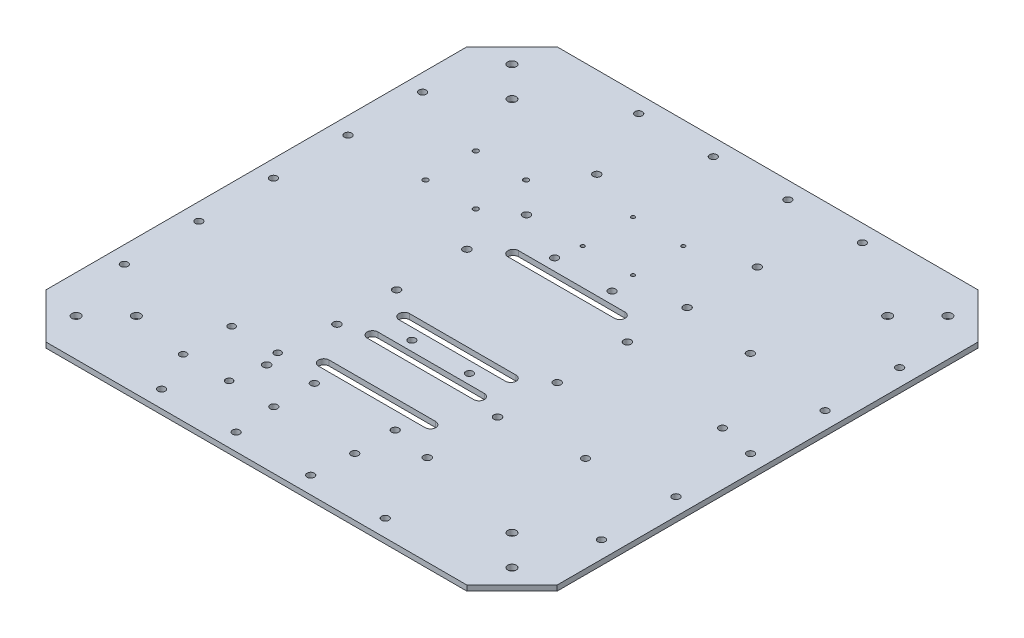
SolidWorks part; units mm, degrees
ref_plane "Front Plane" through (0, 0, 0) normal (0, 0, 1) x (1, 0, 0)
ref_plane "Top Plane" through (0, 0, 0) normal (0, 1, 0) x (1, 0, 0)
ref_plane "Right Plane" through (0, 0, 0) normal (1, 0, 0) x (0, 0, -1)
sketch "Sketch1" plane through (0, 0, 0) normal (0, 1, 0) x (1, 0, 0)
  line L0 (-121.2861, 45.3182) -> (-94.3453, 72.259)
  line L1 (-121.2861, 72.259) -> (183.5139, 72.259)
  line L2 (-121.2861, 72.259) -> (-121.2861, -232.541)
  line L3 (-121.2861, -232.541) -> (183.5139, -232.541)
  line L4 (183.5139, 72.259) -> (183.5139, -232.541)
  line L5 (31.1139, 95.069) -> (31.1139, -294.9418) construction
  line L6 (-146.0448, -80.141) -> (218.038, -80.141) construction
  line L7 (183.5139, 45.3182) -> (156.5732, 72.259)
  line L8 (183.5139, -205.6003) -> (156.5732, -232.541)
  line L9 (-121.2861, -205.6003) -> (-94.3453, -232.541)
  point P8 (31.1139, 72.259)
  point P11 (-121.2861, -80.141)
  dimension "D1" = 304.8
  dimension "D2" = 304.8
  dimension "D3" = 45
  dimension "D4" = 38.1
extrude "Boss-Extrude1" add sketch "Sketch1" along normal blind 3.175
sketch "Sketch2" plane through (0, 3.175, 0) normal (0, 1, 0) x (1, 0, 0)
  line L0 (31.1139, 72.259) -> (31.1139, -287.8465) construction
  line L1 (-94.3453, 72.259) -> (156.5732, 72.259) construction
  line L2 (183.5139, -80.141) -> (-158.2106, -80.141) construction
  line L3 (183.5139, 45.3182) -> (183.5139, -205.6003) construction
  circle A0 centre (13.8419, -37.469) radius 2.159
  circle A1 centre (48.1319, -37.469) radius 2.159
  circle A2 centre (13.8419, -122.559) radius 2.159
  circle A3 centre (48.1319, -122.559) radius 2.159
  dimension "D5" = 4.318
  dimension "D6" = 4.318
  dimension "D7" = 4.318
  dimension "D8" = 4.318
  dimension "D1" = 17.272
  dimension "D2" = 34.29
  dimension "D3" = 85.09
  dimension "D4" = 42.672
extrude "Cut-Extrude1" cut sketch "Sketch2" against normal through all
sketch "Sketch4" plane through (0, 3.175, 0) normal (0, 1, 0) x (1, 0, 0)
  line L0 (-0.6361, -47.641) -> (62.8639, -47.641) construction
  line L1 (-0.6361, -44.466) -> (62.8639, -44.466)
  line L2 (-0.6361, -50.816) -> (62.8639, -50.816)
  line L3 (-0.6361, -112.641) -> (62.8639, -112.641) construction
  line L4 (-0.6361, -109.466) -> (62.8639, -109.466)
  line L5 (-0.6361, -115.816) -> (62.8639, -115.816)
  line L6 (183.5139, 45.3182) -> (183.5139, -205.6003) construction
  line L8 (-121.2861, -80.141) -> (183.5139, -80.141) construction
  line L9 (-121.2861, 45.3182) -> (-121.2861, -205.6003) construction
  line L11 (-0.6361, -131.576) -> (62.8639, -131.576) construction
  line L12 (-0.6361, -128.401) -> (62.8639, -128.401)
  line L13 (-0.6361, -134.751) -> (62.8639, -134.751)
  line L14 (-0.6361, -160.576) -> (62.8639, -160.576) construction
  line L15 (-0.6361, -157.401) -> (62.8639, -157.401)
  line L16 (-0.6361, -163.751) -> (62.8639, -163.751)
  line L17 (31.1139, -47.641) -> (31.1139, -112.641) construction
  arc A0 (-0.6361, -44.466) -> (-0.6361, -50.816) centre (-0.6361, -47.641) ccw
  arc A1 (62.8639, -50.816) -> (62.8639, -44.466) centre (62.8639, -47.641) ccw
  arc A2 (-0.6361, -109.466) -> (-0.6361, -115.816) centre (-0.6361, -112.641) ccw
  arc A3 (62.8639, -115.816) -> (62.8639, -109.466) centre (62.8639, -112.641) ccw
  arc A5 (-0.6361, -128.401) -> (-0.6361, -134.751) centre (-0.6361, -131.576) ccw
  arc A6 (62.8639, -134.751) -> (62.8639, -128.401) centre (62.8639, -131.576) ccw
  arc A7 (-0.6361, -157.401) -> (-0.6361, -163.751) centre (-0.6361, -160.576) ccw
  arc A8 (62.8639, -163.751) -> (62.8639, -157.401) centre (62.8639, -160.576) ccw
  point P2 (31.1139, -47.641)
  point P7 (31.1139, -112.641)
  point P14 (183.5139, -80.141)
  point P15 (31.1139, 72.259)
  point P18 (31.1139, -80.141)
  point P19 (31.1139, -80.141)
  point P28 (31.1139, -131.576)
  point P33 (31.1139, -160.576)
  point P40 (0, 0)
  point P41 (31.1139, -30.0806)
  point P42 (31.1139, 72.259)
  point P43 (31.1139, -28.4758)
  dimension "D1" = 63.5
  dimension "D2" = 63.5
  dimension "D3" = 6.35
  dimension "D4" = 6.35
  dimension "D5" = 65
  dimension "D7" = 63.5
  dimension "D8" = 63.5
  dimension "D9" = 6.35
  dimension "D10" = 6.35
  dimension "D11" = 29
  dimension "D12" = 48.26
extrude "Cut-Extrude2" cut sketch "Sketch4" against normal through all
sketch "Sketch7" plane through (0, 3.175, 0) normal (0, 1, 0) x (1, 0, 0)
  line L0 (-49.9121, 83.1696) -> (-49.9121, -30.4318) construction
  line L1 (-121.2861, -80.141) -> (183.5139, -80.141) construction
  line L2 (-121.2861, 45.3182) -> (-121.2861, -205.6003) construction
  line L3 (183.5139, 45.3182) -> (183.5139, -205.6003) construction
  line L4 (31.1139, 72.259) -> (31.1139, -252.674) construction
  line L5 (-94.3453, 72.259) -> (156.5732, 72.259) construction
  circle A0 centre (-34.9261, -5.719) radius 1.524
  circle A1 centre (-34.9261, -35.691) radius 1.524
  circle A2 centre (-64.8981, -35.691) radius 1.524
  circle A3 centre (-64.8981, -5.719) radius 1.524
  dimension "D1" = 3.048
  dimension "D2" = 14.986
  dimension "D4" = 29.972
  dimension "D3" = 3.048
  dimension "D5" = 44.45
  dimension "D6" = 66.04
  dimension "D7" = 14.986
extrude "Cut-Extrude3" cut sketch "Sketch7" against normal through all
sketch "Sketch8" plane through (0, 3.175, 0) normal (0, 1, 0) x (1, 0, 0)
  line L0 (-94.3453, -232.541) -> (156.5732, -232.541) construction
  line L1 (183.5139, 45.3182) -> (183.5139, -205.6003) construction
  circle A0 centre (73.0239, -207.649) radius 1.524
  circle A1 centre (73.0239, -177.169) radius 1.524
  circle A2 centre (96.8999, -207.649) radius 1.524
  circle A3 centre (96.8999, -177.169) radius 1.524
  dimension "D1" = 3.048
  dimension "D2" = 30.48
  dimension "D3" = 23.876
  dimension "D4" = 24.892
  dimension "D5" = 86.614
extrude "Cut-Extrude4" [suppressed] cut sketch "Sketch8" against normal through all and the other way through all
sketch "Sketch10" plane through (0, 0, 0) normal (0, -1, 0) x (1, 0, 0)
  line L0 (-94.3453, 232.541) -> (156.5732, 232.541) construction
  line L1 (31.1139, 232.541) -> (31.1139, 128.7119) construction
  line L2 (-0.6361, 163.751) -> (62.8639, 163.751) construction
  circle A0 centre (6.9839, 198.041) radius 2.159
  circle A1 centre (55.2439, 198.041) radius 2.159
  circle A2 centre (6.9839, 173.911) radius 2.159
  circle A3 centre (55.2439, 173.911) radius 2.159
  dimension "D1" = 4.318
  dimension "D2" = 48.26
  dimension "D4" = 10.16
  dimension "D6" = 4.318
  dimension "D7" = 4.318
  dimension "D8" = 4.318
  dimension "D3" = 24.13
  dimension "D5" = 24.13
extrude "Cut-Extrude6" cut sketch "Sketch10" against normal through all
sketch "Sketch9" plane through (0, 0, 0) normal (0, -1, 0) x (-1, 0, 0)
  line L1 (121.2861, -80.141) -> (-327.4314, -80.141) construction
  line L2 (33.4021, -47.3693) -> (33.4021, -130.2963) construction
  line L3 (-31.1139, 72.259) -> (-31.1139, -331.7119) construction
  line L4 (94.3453, 72.259) -> (-156.5732, 72.259) construction
  line L7 (121.2861, 45.3182) -> (121.2861, -205.6003) construction
  circle A0 centre (47.1181, -197.997) radius 2.032
  circle A1 centre (19.6861, -197.997) radius 2.032
  circle A2 centre (47.1181, -169.041) radius 2.032
  circle A3 centre (19.6861, -169.041) radius 2.032
  dimension "D1" = 4.064
  dimension "D9" = 4.064
  dimension "D2" = 50.8
  dimension "D3" = 28.956
  dimension "D4" = 88.9
  dimension "D8" = 13.716
extrude "Cut-Extrude5" cut sketch "Sketch9" against normal through all
sketch "Sketch13" plane through (0, 0, 0) normal (0, -1, 0) x (1, 0, 0)
  line L0 (31.1139, -72.259) -> (31.1139, 261.4711) construction
  line L1 (-94.3453, -72.259) -> (156.5732, -72.259) construction
  line L2 (-121.2861, 80.141) -> (239.2508, 80.141) construction
  line L3 (-121.2861, -45.3182) -> (-121.2861, 205.6003) construction
  circle A0 centre (16.1139, 22.991) radius 1.1
  circle A1 centre (16.1139, -7.009) radius 1.1
  circle A2 centre (46.1139, -7.009) radius 1.1
  circle A3 centre (46.1139, 22.991) radius 1.1
  point P16 (0, 0)
  dimension "D1" = 2.2
  dimension "D2" = 2.2
  dimension "D3" = 30
  dimension "D4" = 15
  dimension "D5" = 57.15
extrude "Cut-Extrude8" cut sketch "Sketch13" against normal through all
sketch "Sketch14" plane through (0, 0, 0) normal (0, -1, 0) x (1, 0, 0)
  line L0 (31.1139, 232.541) -> (31.1139, -154.5354) construction
  line L1 (-94.3453, 232.541) -> (156.5732, 232.541) construction
  line L2 (-121.2861, 80.141) -> (331.9066, 80.141) construction
  line L3 (-121.2861, -45.3182) -> (-121.2861, 205.6003) construction
  line L4 (-121.2861, 205.6003) -> (-94.3453, 232.541) construction
  line L5 (-224.559, -175.5319) -> (286.7869, 335.814) construction
  line L6 (-224.559, -175.5319) -> (286.7869, -175.5319) construction
  line L7 (-224.559, -175.5319) -> (-224.559, 335.814) construction
  line L8 (-121.2861, 205.6003) -> (-94.3453, 232.541) construction
  line L9 (-107.8157, 219.0706) -> (-48.5429, 159.7979) construction
  line L10 (-224.559, 335.814) -> (286.7869, 335.814) construction
  line L11 (286.7869, -175.5319) -> (286.7869, 335.814) construction
  line L12 (286.7869, -175.5319) -> (-224.559, 335.814) construction
  line L14 (-121.2861, -45.3182) -> (-94.3453, -72.259) construction
  line L21 (-224.559, -175.5319) -> (-107.8157, -58.7886) construction
  line L22 (170.0436, -58.7886) -> (286.7869, -175.5319) construction
  line L23 (183.5139, -45.3182) -> (156.5732, -72.259) construction
  line L24 (170.0436, 219.0706) -> (286.7869, 335.814) construction
  line L25 (183.5139, 205.6003) -> (156.5732, 232.541) construction
  line L26 (-224.559, 335.814) -> (-107.8157, 219.0706) construction
  circle A1 centre (-98.8354, 210.0904) radius 2.54
  circle A3 centre (-80.8749, 192.1299) radius 2.54
  circle A4 centre (143.1028, 192.1299) radius 2.54
  circle A7 centre (161.0633, 210.0904) radius 2.54
  circle A8 centre (-98.8354, -49.8083) radius 2.54
  circle A11 centre (-80.8749, -31.8478) radius 2.54
  circle A14 centre (161.0633, -49.8083) radius 2.54
  circle A15 centre (143.1028, -31.8478) radius 2.54
  point P8 (31.1139, 80.141)
  point P30 (286.7869, 80.141)
  point P33 (-107.8157, -58.7886)
  point P36 (31.1139, -175.5319)
  dimension "D3" = 5.08
  dimension "D6" = 5.08
  dimension "D1" = 12.7
  dimension "D2" = 165.1
  dimension "D9" = 25.4
extrude "Cut-Extrude9" cut sketch "Sketch14" against normal through all
sketch "Sketch15" plane through (0, 0, 0) normal (0, -1, 0) x (1, 0, 0)
  line L0 (31.1139, 232.541) -> (31.1139, 125.875) construction
  line L1 (-94.3453, 232.541) -> (156.5732, 232.541) construction
  line L2 (-121.2861, 80.141) -> (75.4631, 80.141) construction
  line L3 (-121.2861, -45.3182) -> (-121.2861, 205.6003) construction
  circle A0 centre (8.8889, 222.381) radius 2.159
  circle A1 centre (-35.5611, 222.381) radius 2.159
  circle A2 centre (-111.1261, 80.141) radius 2.159
  circle A3 centre (-111.1261, 124.591) radius 2.159
  circle A4 centre (-111.1261, 169.041) radius 2.159
  circle A5 centre (173.3539, 169.041) radius 2.159
  circle A6 centre (173.3539, 124.591) radius 2.159
  circle A7 centre (173.3539, 80.141) radius 2.159
  circle A8 centre (97.7889, 222.381) radius 2.159
  circle A9 centre (53.3389, 222.381) radius 2.159
  circle A10 centre (53.3389, -62.099) radius 2.159
  circle A11 centre (97.7889, -62.099) radius 2.159
  circle A12 centre (173.3539, 35.691) radius 2.159
  circle A13 centre (173.3539, -8.759) radius 2.159
  circle A14 centre (-111.1261, -8.759) radius 2.159
  circle A15 centre (-111.1261, 35.691) radius 2.159
  circle A16 centre (-35.5611, -62.099) radius 2.159
  circle A17 centre (8.8889, -62.099) radius 2.159
  dimension "D3" = 4.318
  dimension "D4" = 4.318
  dimension "D8" = 4.318
  dimension "D9" = 4.318
  dimension "D10" = 4.318
  dimension "D1" = 22.225
  dimension "D2" = 44.45
  dimension "D5" = 10.16
  dimension "D6" = 44.45
  dimension "D7" = 44.45
  dimension "D11" = 10.16
extrude "Cut-Extrude10" cut sketch "Sketch15" against normal through all
sketch "Sketch16" plane through (0, 0, 0) normal (0, -1, 0) x (-1, 0, 0)
  line L0 (-31.1139, 72.259) -> (-31.1139, -323.0503) construction
  line L1 (-101.2179, -121.924) -> (-141.8579, -121.924)
  line L2 (-101.2179, -121.924) -> (-101.2179, -38.358)
  line L3 (-101.2179, -38.358) -> (-141.8579, -38.358)
  line L4 (-141.8579, -121.924) -> (-141.8579, -38.358)
  line L6 (94.3453, 72.259) -> (-156.5732, 72.259) construction
  line L7 (121.2861, -80.141) -> (-312.3855, -80.141) construction
  line L8 (121.2861, 45.3182) -> (121.2861, -205.6003) construction
  circle A0 centre (-126.6179, -131.83) radius 2.159
  circle A1 centre (-121.5379, -28.452) radius 2.159
  circle A2 centre (-151.7639, -75.274) radius 2.159
  point P18 (-141.8579, -80.141)
  dimension "D3" = 9.906
  dimension "D4" = 9.906
  dimension "D5" = 9.906
  dimension "D6" = 15.24
  dimension "D7" = 20.32
  dimension "D8" = 46.65
  dimension "D9" = 4.318
  dimension "D10" = 4.318
  dimension "D11" = 4.318
  dimension "D1" = 83.566
  dimension "D2" = 40.64
  dimension "D12" = 120.65
  dimension "D13" = 0
extrude "Cut-Extrude11" cut sketch "Sketch16" against normal through all contours A2 | A0 | A1
sketch "Sketch17" plane through (0, 3.175, 0) normal (0, 1, 0) x (1, 0, 0)
  line L2 (31.1139, 72.259) -> (31.1139, -395.818) construction
  line L3 (-94.3453, 72.259) -> (156.5732, 72.259) construction
  line L4 (183.5139, -80.141) -> (-127.1454, -80.141) construction
  line L5 (183.5139, 45.3182) -> (183.5139, -205.6003) construction
  circle A12 centre (78.9929, -178.566) radius 2.2225
  circle A13 centre (-16.7651, -178.566) radius 2.2225
  circle A14 centre (78.9929, -136.656) radius 2.2225
  circle A15 centre (-16.7651, -136.656) radius 2.2225
  circle A16 centre (78.9929, -101.096) radius 2.2225
  circle A17 centre (-16.7651, -101.096) radius 2.2225
  circle A18 centre (78.9929, -59.186) radius 2.2225
  circle A19 centre (-16.7651, -59.186) radius 2.2225
  circle A20 centre (78.9929, -23.626) radius 2.2225
  circle A21 centre (-16.7651, -23.626) radius 2.2225
  circle A22 centre (78.9929, 18.284) radius 2.2225
  circle A23 centre (-16.7651, 18.284) radius 2.2225
  circle A24 centre (-16.7651, 18.284) radius 2.2225
  circle A25 centre (78.9929, 18.284) radius 2.2225
  circle A26 centre (-16.7651, -23.626) radius 2.2225
  circle A27 centre (78.9929, -23.626) radius 2.2225
  circle A28 centre (-16.7651, -59.186) radius 2.2225
  circle A29 centre (78.9929, -59.186) radius 2.2225
  circle A30 centre (-16.7651, -101.096) radius 2.2225
  circle A31 centre (78.9929, -101.096) radius 2.2225
  circle A32 centre (-16.7651, -136.656) radius 2.2225
  circle A33 centre (78.9929, -136.656) radius 2.2225
  circle A34 centre (-16.7651, -178.566) radius 2.2225
  dimension "D1" = 4.445
  dimension "D2" = 4.445
  dimension "D3" = 4.445
  dimension "D4" = 4.445
  dimension "D5" = 4.445
  dimension "D6" = 4.445
  dimension "D7" = 4.445
  dimension "D8" = 4.445
  dimension "D9" = 4.445
  dimension "D10" = 4.445
  dimension "D11" = 4.445
  dimension "D12" = 4.445
  dimension "D25" = 56.515
  dimension "D24" = 56.515
  dimension "D13" = 95.758
  dimension "D14" = 41.91
  dimension "D15" = 95.758
  dimension "D16" = 41.91
  dimension "D17" = 95.758
  dimension "D18" = 41.91
  dimension "D19" = 47.879
  dimension "D20" = 47.879
  dimension "D21" = 47.879
  dimension "D22" = 20.955
extrude "Cut-Extrude13" cut sketch "Sketch17" against normal through all contours A23 | A22 | A20 | A21 | A18 | A19 | A17 | A16 | A12 | A14 | A15 | A13
sketch "Sketch18" plane through (0, 3.175, 0) normal (0, 1, 0) x (1, 0, 0)
  line L0 (-121.2861, -205.6003) -> (-94.3453, -232.541) construction
  line L1 (-98.8354, -228.0509) -> (-116.7959, -210.0904)
  line L2 (-98.8354, -228.0509) -> (-62.9144, -192.1299)
  line L3 (-62.9144, -192.1299) -> (-80.8749, -174.1694)
  line L4 (-116.7959, -210.0904) -> (-80.8749, -174.1694)
  line L5 (31.1139, 72.259) -> (31.1139, -264.9481) construction
  line L6 (-94.3453, 72.259) -> (156.5732, 72.259) construction
  line L7 (183.5139, -80.141) -> (-155.4453, -80.141) construction
  line L8 (183.5139, 45.3182) -> (183.5139, -205.6003) construction
  line L9 (-116.7959, 49.8083) -> (-80.8749, 13.8873)
  line L10 (-62.9144, 31.8478) -> (-80.8749, 13.8873)
  line L11 (-98.8354, 67.7688) -> (-62.9144, 31.8478)
  line L12 (-98.8354, 67.7688) -> (-116.7959, 49.8083)
  line L13 (161.0633, 67.7688) -> (179.0238, 49.8083)
  line L14 (161.0633, 67.7688) -> (125.1423, 31.8478)
  line L15 (125.1423, 31.8478) -> (143.1028, 13.8873)
  line L16 (179.0238, 49.8083) -> (143.1028, 13.8873)
  line L17 (179.0238, -210.0904) -> (143.1028, -174.1694)
  line L18 (125.1423, -192.1299) -> (143.1028, -174.1694)
  line L19 (161.0633, -228.0509) -> (125.1423, -192.1299)
  line L20 (161.0633, -228.0509) -> (179.0238, -210.0904)
  point P11 (-107.8157, -219.0706)
  point P12 (-107.8157, -219.0706)
  dimension "D1" = 50.8
  dimension "D2" = 25.4
